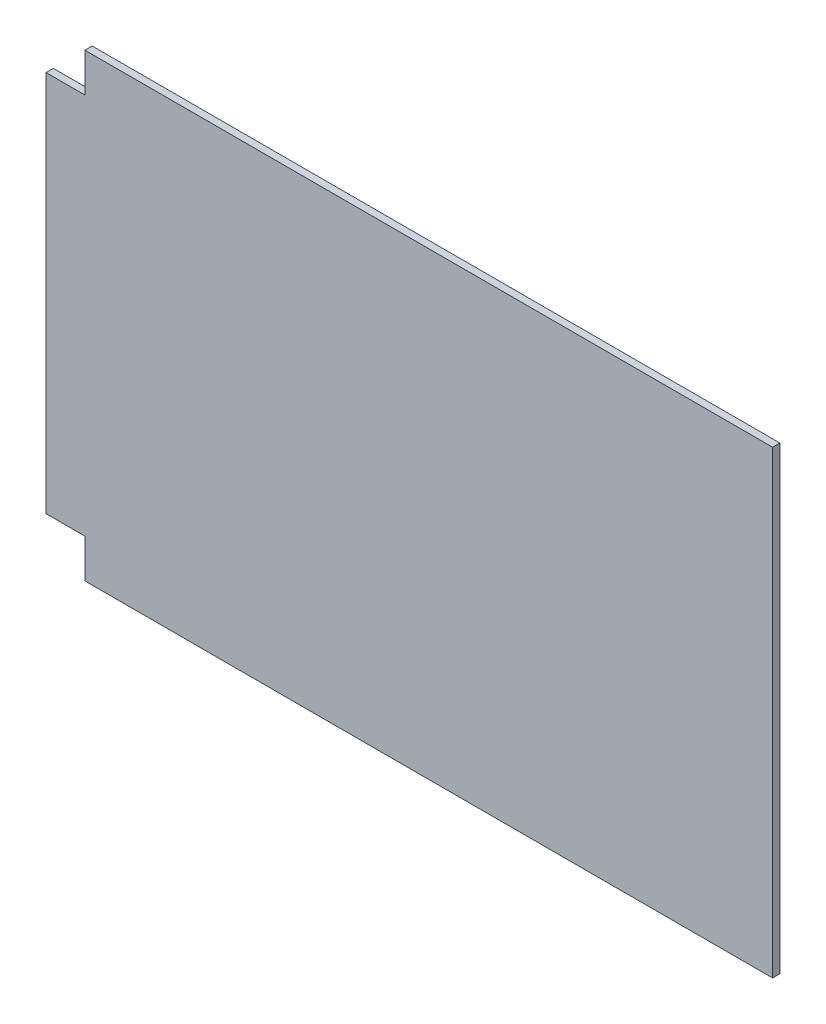
SolidWorks part; units mm, degrees
ref_plane "前基準面" through (0, 0, 0) normal (0, 0, 1) x (1, 0, 0)
ref_plane "上基準面" through (0, 0, 0) normal (0, 1, 0) x (1, 0, 0)
ref_plane "右基準面" through (0, 0, 0) normal (1, 0, 0) x (0, 0, -1)
sketch "草圖1" plane through (0, 0, 0) normal (0, 0, 1) x (1, 0, 0)
  line L1 (-250.4, 150.4) -> (250.4, 150.4)
  line L2 (-250.4, 150.4) -> (-250.4, -150.4)
  line L3 (-250.4, -150.4) -> (250.4, -150.4)
  line L4 (250.4, 150.4) -> (250.4, -150.4)
  line L5 (-250.4, 150.4) -> (250.4, -150.4) construction
  line L6 (-250.4, -150.4) -> (250.4, 150.4) construction
  point P0 (0, 0)
  dimension "D1" = 500.8
  dimension "D2" = 300.8
extrude "填料-伸長1" add sketch "草圖1" along normal blind 4.75 contours L1 L4 L3 L2
sketch "草圖2" plane through (0, 0, 0) normal (0, 0, -1) x (-1, 0, 0)
  line L1 (-250.4, 150.4) -> (-225, 150.4)
  line L2 (-250.4, 150.4) -> (-250.4, 125)
  line L4 (-225, 150.4) -> (-225, 125)
  line L5 (-250.4, -150.4) -> (-225, -150.4)
  line L6 (-250.4, -150.4) -> (-250.4, -125)
  line L8 (-225, -150.4) -> (-225, -125)
  line L9 (250.4, 150.4) -> (225, 150.4)
  line L10 (250.4, 150.4) -> (250.4, 125)
  line L11 (250.4, 125) -> (225, 125)
  line L12 (225, 150.4) -> (225, 125)
  line L13 (250.4, -150.4) -> (225, -150.4)
  line L14 (250.4, -150.4) -> (250.4, -125)
  line L15 (250.4, -125) -> (225, -125)
  line L16 (225, -150.4) -> (225, -125)
  line L17 (-225, 125) -> (-225, -125)
  line L19 (-250.4, 125) -> (-250.4, -125)
  dimension "D1" = 25.4
  dimension "D2" = 25.4
  dimension "D3" = 25.4
  dimension "D4" = 25.4
  dimension "D5" = 25.4
  dimension "D6" = 25.4
  dimension "D7" = 25.4
  dimension "D8" = 25.4
extrude "除料-伸長1" cut sketch "草圖2" against normal blind 10
